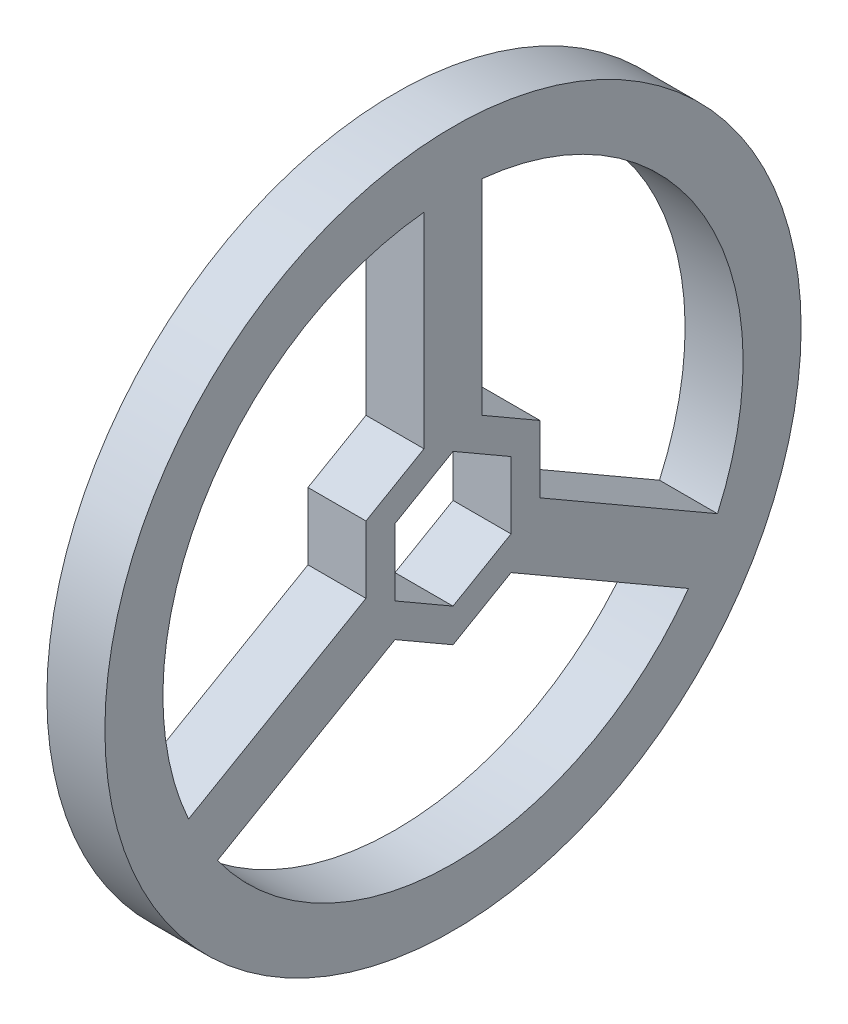
SolidWorks part; units mm, degrees
ref_plane "Front Plane" through (0, 0, 0) normal (0, 0, 1) x (1, 0, 0)
ref_plane "Top Plane" through (0, 0, 0) normal (0, 1, 0) x (1, 0, 0)
ref_plane "Right Plane" through (0, 0, 0) normal (1, 0, 0) x (0, 0, -1)
sketch "Sketch1" plane through (0, 0, 0) normal (1, 0, 0) x (0, 0, -1)
  line L0 (0, 0) -> (0, 30) construction
  line L1 (-2.5, 0) -> (-2.5, 30)
  line L2 (2.5, 0) -> (2.5, 30)
  line L3 (-1.25, -2.1651) -> (24.7308, -17.1651)
  line L4 (1.25, 2.1651) -> (27.2308, -12.8349)
  line L5 (0, 0) -> (25.9808, -15) construction
  line L6 (-1.25, 2.1651) -> (-27.2308, -12.8349)
  line L7 (1.25, -2.1651) -> (-24.7308, -17.1651)
  line L8 (0, 0) -> (-25.9808, -15) construction
  line L9 (7.5, 4.3301) -> (0, 8.6603)
  line L10 (0, 5.7735) -> (-5, 2.8868)
  line L11 (-5, 2.8868) -> (-5, -2.8868)
  line L12 (-5, -2.8868) -> (0, -5.7735)
  line L13 (0, -5.7735) -> (5, -2.8868)
  line L14 (5, -2.8868) -> (5, 2.8868)
  line L15 (5, 2.8868) -> (0, 5.7735)
  line L16 (0, 8.6603) -> (-7.5, 4.3301)
  line L17 (-7.5, 4.3301) -> (-7.5, -4.3301)
  line L18 (-7.5, -4.3301) -> (0, -8.6603)
  line L19 (0, -8.6603) -> (7.5, -4.3301)
  line L20 (7.5, -4.3301) -> (7.5, 4.3301)
  circle A0 centre (0, 0) radius 30
  arc A1 (-2.5, 0) -> (2.5, 0) centre (0, 0) ccw
  arc A2 (2.5, 30) -> (-2.5, 30) centre (0, 30) ccw
  circle A3 centre (0, 0) radius 25
  arc A4 (1.25, 2.1651) -> (-1.25, -2.1651) centre (0, 0) ccw
  arc A5 (24.7308, -17.1651) -> (27.2308, -12.8349) centre (25.9808, -15) ccw
  arc A6 (1.25, -2.1651) -> (-1.25, 2.1651) centre (0, 0) ccw
  arc A7 (-27.2308, -12.8349) -> (-24.7308, -17.1651) centre (-25.9808, -15) ccw
  circle A8 centre (0, 0) radius 5 construction
  point P3 (0, 15)
  point P11 (12.9904, -7.5)
  point P19 (-12.9904, -7.5)
  point P25 (0, 0)
  dimension "D1" = 60
  dimension "D3" = 2.5
  dimension "D4" = 5
  dimension "D6" = 10
  dimension "D2" = 30
  dimension "D7" = 2.5
  dimension "D5" = 3
extrude "Boss-Extrude1" add sketch "Sketch1" along normal blind 5 contours A3 L4 A0 L2 | A3 L1 A0 L6 | A3 L2 A0 L1 | A3 L3 A0 L4 | A3 L7 A0 L3 | A3 L6 A0 L7 | L3 A3 L4 L20 L19 | L6 A3 L7 L18 L17 | L2 A3 L1 L16 L9 | L16 L17 L6 L11 L10 L1 | L9 L16 L1 L10 L15 L2 | L4 L20 L9 L2 L15 L14 | L19 L20 L4 L14 L13 L3 | L18 L19 L3 L13 L12 L7 | L17 L18 L7 L12 L11 L6
